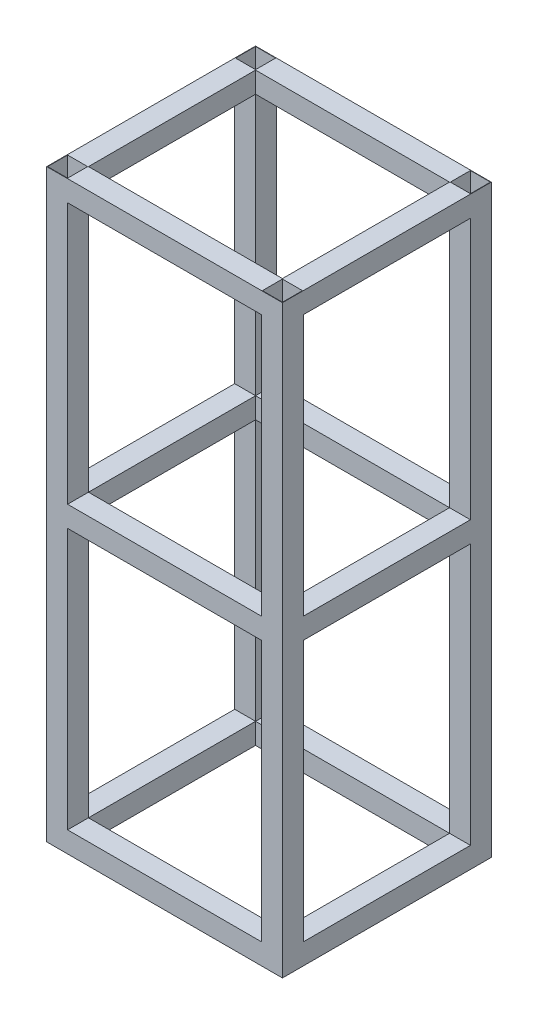
SolidWorks part; units mm, degrees
ref_plane "Front Plane" through (0, 0, 0) normal (0, 0, 1) x (1, 0, 0)
ref_plane "Top Plane" through (0, 0, 0) normal (0, 1, 0) x (1, 0, 0)
ref_plane "Right Plane" through (0, 0, 0) normal (1, 0, 0) x (0, 0, -1)
sketch "Sketch1" plane through (0, 0, 0) normal (0, 1, 0) x (1, 0, 0)
  line L1 (-877.7127, 777.7127) -> (-722.2873, 777.7127)
  line L2 (-877.7127, 777.7127) -> (-877.7127, 622.2873)
  line L3 (-877.7127, 622.2873) -> (-722.2873, 622.2873)
  line L4 (-722.2873, 777.7127) -> (-722.2873, 622.2873)
  line L6 (-874.7127, 774.7127) -> (-725.2873, 774.7127)
  line L7 (-874.7127, 774.7127) -> (-874.7127, 625.2873)
  line L8 (-874.7127, 625.2873) -> (-725.2873, 625.2873)
  line L9 (-725.2873, 774.7127) -> (-725.2873, 625.2873)
extrude "Boss-Extrude1" add sketch "Sketch1" along normal blind 4355.4254 from offset 2177.7127
sketch "Sketch2" plane through (0, 0, 0) normal (0, 1, 0) x (1, 0, 0)
  line L1 (-877.7127, -622.2873) -> (-722.2873, -622.2873)
  line L2 (-877.7127, -622.2873) -> (-877.7127, -777.7127)
  line L3 (-877.7127, -777.7127) -> (-722.2873, -777.7127)
  line L4 (-722.2873, -622.2873) -> (-722.2873, -777.7127)
  line L6 (-874.7127, -625.2873) -> (-725.2873, -625.2873)
  line L7 (-874.7127, -625.2873) -> (-874.7127, -774.7127)
  line L8 (-874.7127, -774.7127) -> (-725.2873, -774.7127)
  line L9 (-725.2873, -625.2873) -> (-725.2873, -774.7127)
extrude "Boss-Extrude2" add sketch "Sketch2" along normal blind 4355.4254 from offset 2177.7127
sketch "Sketch3" plane through (0, 0, 0) normal (0, 1, 0) x (1, 0, 0)
  line L1 (722.2873, 777.7127) -> (877.7127, 777.7127)
  line L2 (722.2873, 777.7127) -> (722.2873, 622.2873)
  line L3 (722.2873, 622.2873) -> (877.7127, 622.2873)
  line L4 (877.7127, 777.7127) -> (877.7127, 622.2873)
  line L6 (725.2873, 774.7127) -> (874.7127, 774.7127)
  line L7 (725.2873, 774.7127) -> (725.2873, 625.2873)
  line L8 (725.2873, 625.2873) -> (874.7127, 625.2873)
  line L9 (874.7127, 774.7127) -> (874.7127, 625.2873)
extrude "Boss-Extrude3" add sketch "Sketch3" along normal blind 4355.4254 from offset 2177.7127
sketch "Sketch4" plane through (0, 0, 0) normal (0, 1, 0) x (1, 0, 0)
  line L1 (722.2873, -622.2873) -> (877.7127, -622.2873)
  line L2 (722.2873, -622.2873) -> (722.2873, -777.7127)
  line L3 (722.2873, -777.7127) -> (877.7127, -777.7127)
  line L4 (877.7127, -622.2873) -> (877.7127, -777.7127)
  line L6 (725.2873, -625.2873) -> (874.7127, -625.2873)
  line L7 (725.2873, -625.2873) -> (725.2873, -774.7127)
  line L8 (725.2873, -774.7127) -> (874.7127, -774.7127)
  line L9 (874.7127, -625.2873) -> (874.7127, -774.7127)
extrude "Boss-Extrude4" add sketch "Sketch4" along normal blind 4355.4254 from offset 2177.7127
sketch "Sketch5" plane through (0, 0, 0) normal (1, 0, 0) x (0, 0, -1)
  line L1 (777.7127, -2177.7127) -> (622.2873, -2177.7127)
  line L2 (777.7127, -2177.7127) -> (777.7127, -2022.2873)
  line L3 (777.7127, -2022.2873) -> (622.2873, -2022.2873)
  line L4 (622.2873, -2177.7127) -> (622.2873, -2022.2873)
  line L6 (774.7127, -2174.7127) -> (625.2873, -2174.7127)
  line L7 (774.7127, -2174.7127) -> (774.7127, -2025.2873)
  line L8 (774.7127, -2025.2873) -> (625.2873, -2025.2873)
  line L9 (625.2873, -2174.7127) -> (625.2873, -2025.2873)
extrude "Boss-Extrude5" add sketch "Sketch5" along normal blind 1444.5746 from offset 722.2873
sketch "Sketch6" plane through (0, 0, 0) normal (1, 0, 0) x (0, 0, -1)
  line L1 (-622.2873, -2177.7127) -> (-777.7127, -2177.7127)
  line L2 (-622.2873, -2177.7127) -> (-622.2873, -2022.2873)
  line L3 (-622.2873, -2022.2873) -> (-777.7127, -2022.2873)
  line L4 (-777.7127, -2177.7127) -> (-777.7127, -2022.2873)
  line L6 (-625.2873, -2174.7127) -> (-774.7127, -2174.7127)
  line L7 (-625.2873, -2174.7127) -> (-625.2873, -2025.2873)
  line L8 (-625.2873, -2025.2873) -> (-774.7127, -2025.2873)
  line L9 (-774.7127, -2174.7127) -> (-774.7127, -2025.2873)
extrude "Boss-Extrude6" add sketch "Sketch6" along normal blind 1444.5746 from offset 722.2873
sketch "Sketch7" plane through (0, 0, 0) normal (0, 0, 1) x (1, 0, 0)
  line L1 (-877.7127, -2177.7127) -> (-722.2873, -2177.7127)
  line L2 (-877.7127, -2177.7127) -> (-877.7127, -2022.2873)
  line L3 (-877.7127, -2022.2873) -> (-722.2873, -2022.2873)
  line L4 (-722.2873, -2177.7127) -> (-722.2873, -2022.2873)
  line L6 (-874.7127, -2174.7127) -> (-725.2873, -2174.7127)
  line L7 (-874.7127, -2174.7127) -> (-874.7127, -2025.2873)
  line L8 (-874.7127, -2025.2873) -> (-725.2873, -2025.2873)
  line L9 (-725.2873, -2174.7127) -> (-725.2873, -2025.2873)
extrude "Boss-Extrude7" add sketch "Sketch7" along normal blind 1244.5746 from offset 622.2873
sketch "Sketch8" plane through (0, 0, 0) normal (0, 0, 1) x (1, 0, 0)
  line L1 (722.2873, -2177.7127) -> (877.7127, -2177.7127)
  line L2 (722.2873, -2177.7127) -> (722.2873, -2022.2873)
  line L3 (722.2873, -2022.2873) -> (877.7127, -2022.2873)
  line L4 (877.7127, -2177.7127) -> (877.7127, -2022.2873)
  line L6 (725.2873, -2174.7127) -> (874.7127, -2174.7127)
  line L7 (725.2873, -2174.7127) -> (725.2873, -2025.2873)
  line L8 (725.2873, -2025.2873) -> (874.7127, -2025.2873)
  line L9 (874.7127, -2174.7127) -> (874.7127, -2025.2873)
extrude "Boss-Extrude8" add sketch "Sketch8" along normal blind 1244.5746 from offset 622.2873
sketch "Sketch9" plane through (0, 0, 0) normal (1, 0, 0) x (0, 0, -1)
  line L1 (777.7127, -77.7127) -> (622.2873, -77.7127)
  line L2 (777.7127, -77.7127) -> (777.7127, 77.7127)
  line L3 (777.7127, 77.7127) -> (622.2873, 77.7127)
  line L4 (622.2873, -77.7127) -> (622.2873, 77.7127)
  line L6 (774.7127, -74.7127) -> (625.2873, -74.7127)
  line L7 (774.7127, -74.7127) -> (774.7127, 74.7127)
  line L8 (774.7127, 74.7127) -> (625.2873, 74.7127)
  line L9 (625.2873, -74.7127) -> (625.2873, 74.7127)
extrude "Boss-Extrude9" add sketch "Sketch9" along normal blind 1444.5746 from offset 722.2873
sketch "Sketch10" plane through (0, 0, 0) normal (1, 0, 0) x (0, 0, -1)
  line L1 (-622.2873, -77.7127) -> (-777.7127, -77.7127)
  line L2 (-622.2873, -77.7127) -> (-622.2873, 77.7127)
  line L3 (-622.2873, 77.7127) -> (-777.7127, 77.7127)
  line L4 (-777.7127, -77.7127) -> (-777.7127, 77.7127)
  line L6 (-625.2873, -74.7127) -> (-774.7127, -74.7127)
  line L7 (-625.2873, -74.7127) -> (-625.2873, 74.7127)
  line L8 (-625.2873, 74.7127) -> (-774.7127, 74.7127)
  line L9 (-774.7127, -74.7127) -> (-774.7127, 74.7127)
extrude "Boss-Extrude10" add sketch "Sketch10" along normal blind 1444.5746 from offset 722.2873
sketch "Sketch11" plane through (0, 0, 0) normal (0, 0, 1) x (1, 0, 0)
  line L1 (-877.7127, -77.7127) -> (-722.2873, -77.7127)
  line L2 (-877.7127, -77.7127) -> (-877.7127, 77.7127)
  line L3 (-877.7127, 77.7127) -> (-722.2873, 77.7127)
  line L4 (-722.2873, -77.7127) -> (-722.2873, 77.7127)
  line L6 (-874.7127, -74.7127) -> (-725.2873, -74.7127)
  line L7 (-874.7127, -74.7127) -> (-874.7127, 74.7127)
  line L8 (-874.7127, 74.7127) -> (-725.2873, 74.7127)
  line L9 (-725.2873, -74.7127) -> (-725.2873, 74.7127)
extrude "Boss-Extrude11" add sketch "Sketch11" along normal blind 1244.5746 from offset 622.2873
sketch "Sketch12" plane through (0, 0, 0) normal (0, 0, 1) x (1, 0, 0)
  line L1 (722.2873, -77.7127) -> (877.7127, -77.7127)
  line L2 (722.2873, -77.7127) -> (722.2873, 77.7127)
  line L3 (722.2873, 77.7127) -> (877.7127, 77.7127)
  line L4 (877.7127, -77.7127) -> (877.7127, 77.7127)
  line L6 (725.2873, -74.7127) -> (874.7127, -74.7127)
  line L7 (725.2873, -74.7127) -> (725.2873, 74.7127)
  line L8 (725.2873, 74.7127) -> (874.7127, 74.7127)
  line L9 (874.7127, -74.7127) -> (874.7127, 74.7127)
extrude "Boss-Extrude12" add sketch "Sketch12" along normal blind 1244.5746 from offset 622.2873
sketch "Sketch13" plane through (0, 0, 0) normal (1, 0, 0) x (0, 0, -1)
  line L1 (777.7127, 2022.2873) -> (622.2873, 2022.2873)
  line L2 (777.7127, 2022.2873) -> (777.7127, 2177.7127)
  line L3 (777.7127, 2177.7127) -> (622.2873, 2177.7127)
  line L4 (622.2873, 2022.2873) -> (622.2873, 2177.7127)
  line L6 (774.7127, 2025.2873) -> (625.2873, 2025.2873)
  line L7 (774.7127, 2025.2873) -> (774.7127, 2174.7127)
  line L8 (774.7127, 2174.7127) -> (625.2873, 2174.7127)
  line L9 (625.2873, 2025.2873) -> (625.2873, 2174.7127)
extrude "Boss-Extrude13" add sketch "Sketch13" along normal blind 1444.5746 from offset 722.2873
sketch "Sketch14" plane through (0, 0, 0) normal (1, 0, 0) x (0, 0, -1)
  line L1 (-622.2873, 2022.2873) -> (-777.7127, 2022.2873)
  line L2 (-622.2873, 2022.2873) -> (-622.2873, 2177.7127)
  line L3 (-622.2873, 2177.7127) -> (-777.7127, 2177.7127)
  line L4 (-777.7127, 2022.2873) -> (-777.7127, 2177.7127)
  line L6 (-625.2873, 2025.2873) -> (-774.7127, 2025.2873)
  line L7 (-625.2873, 2025.2873) -> (-625.2873, 2174.7127)
  line L8 (-625.2873, 2174.7127) -> (-774.7127, 2174.7127)
  line L9 (-774.7127, 2025.2873) -> (-774.7127, 2174.7127)
extrude "Boss-Extrude14" add sketch "Sketch14" along normal blind 1444.5746 from offset 722.2873
sketch "Sketch15" plane through (0, 0, 0) normal (0, 0, 1) x (1, 0, 0)
  line L1 (-877.7127, 2022.2873) -> (-722.2873, 2022.2873)
  line L2 (-877.7127, 2022.2873) -> (-877.7127, 2177.7127)
  line L3 (-877.7127, 2177.7127) -> (-722.2873, 2177.7127)
  line L4 (-722.2873, 2022.2873) -> (-722.2873, 2177.7127)
  line L6 (-874.7127, 2025.2873) -> (-725.2873, 2025.2873)
  line L7 (-874.7127, 2025.2873) -> (-874.7127, 2174.7127)
  line L8 (-874.7127, 2174.7127) -> (-725.2873, 2174.7127)
  line L9 (-725.2873, 2025.2873) -> (-725.2873, 2174.7127)
extrude "Boss-Extrude15" add sketch "Sketch15" along normal blind 1244.5746 from offset 622.2873
sketch "Sketch16" plane through (0, 0, 0) normal (0, 0, 1) x (1, 0, 0)
  line L1 (722.2873, 2022.2873) -> (877.7127, 2022.2873)
  line L2 (722.2873, 2022.2873) -> (722.2873, 2177.7127)
  line L3 (722.2873, 2177.7127) -> (877.7127, 2177.7127)
  line L4 (877.7127, 2022.2873) -> (877.7127, 2177.7127)
  line L6 (725.2873, 2025.2873) -> (874.7127, 2025.2873)
  line L7 (725.2873, 2025.2873) -> (725.2873, 2174.7127)
  line L8 (725.2873, 2174.7127) -> (874.7127, 2174.7127)
  line L9 (874.7127, 2025.2873) -> (874.7127, 2174.7127)
extrude "Boss-Extrude16" add sketch "Sketch16" along normal blind 1244.5746 from offset 622.2873
